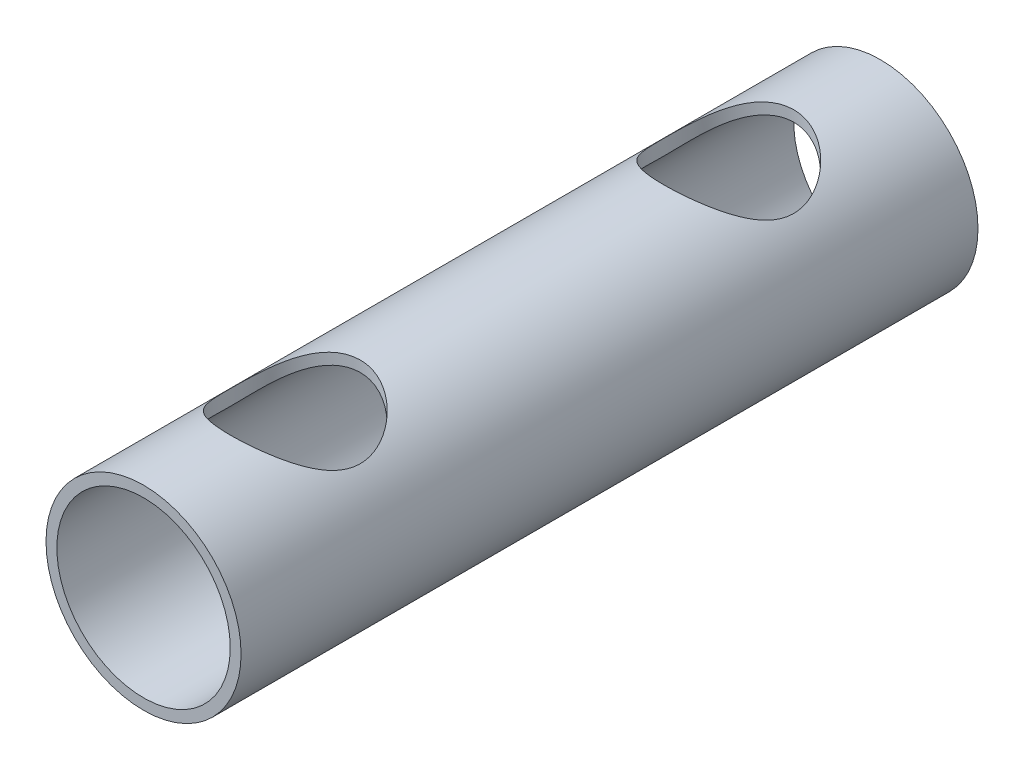
SolidWorks part; units mm, degrees
ref_plane "Front Plane" through (0, 0, 0) normal (0, 0, 1) x (1, 0, 0)
ref_plane "Top Plane" through (0, 0, 0) normal (0, 1, 0) x (1, 0, 0)
ref_plane "Right Plane" through (0, 0, 0) normal (1, 0, 0) x (0, 0, -1)
sketch "Sketch1" plane through (0, 0, 0) normal (0, 0, 1) x (1, 0, 0)
  circle A0 centre (0, 0) radius 50.8
  circle A1 centre (0, 0) radius 57.15
  dimension "D1" = 101.6
  dimension "D2" = 114.3
extrude "Boss-Extrude1" add sketch "Sketch1" along normal blind 431.8
sketch "Sketch2" plane through (0, 0, 0) normal (0, 1, 0) x (1, 0, 0)
  line L0 (50.8, 0) -> (-50.8, 0) construction
  circle A0 centre (0, -88.9) radius 38.1
  circle A1 centre (0, -342.9) radius 38.1
  circle A2 centre (0, -596.9) radius 38.1
  dimension "D1" = 76.2
  dimension "D3" = 76.2
  dimension "D5" = 76.2
  dimension "D2" = 88.9
  dimension "D4" = 254
  dimension "D6" = 254
extrude "Cut-Extrude4" cut sketch "Sketch2" along normal blind 914.4
